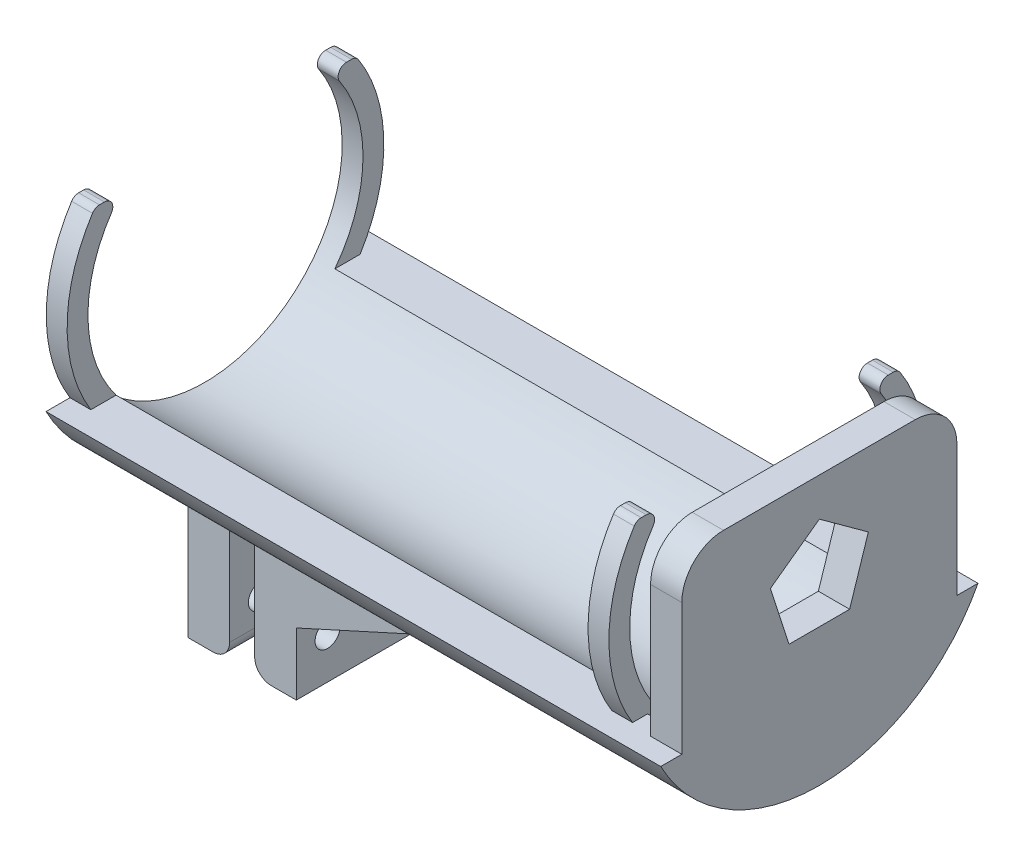
SolidWorks part; units mm, degrees
ref_plane "Front" through (0, 0, 0) normal (0, 0, 1) x (1, 0, 0)
ref_plane "Top" through (0, 0, 0) normal (0, 1, 0) x (1, 0, 0)
ref_plane "Right" through (0, 0, 0) normal (1, 0, 0) x (0, 0, -1)
sketch "Sketch1" plane through (0, 0, 0) normal (1, 0, 0) x (0, 0, -1)
  line L1 (-38.0657, -20) -> (-26.2488, -20)
  line L2 (26.2488, -20) -> (38.0657, -20)
  arc A0 (-26.2488, -20) -> (26.2488, -20) centre (0, 0) ccw
  arc A1 (-38.0657, -20) -> (38.0657, -20) centre (0, 0) ccw
  dimension "D1" = 66
  dimension "D2" = 10
  dimension "D3" = 20
extrude "Boss-Extrude1" add sketch "Sketch1" along normal mid plane 140
sketch "Sketch2" plane through (70, 0, 0) normal (1, 0, 0) x (0, 0, -1)
  line L0 (-31.305, 21.5407) -> (-25, 21.5407)
  line L1 (25, 21.5407) -> (31.305, 21.5407)
  arc A0 (-25, 21.5407) -> (25, 21.5407) centre (0, 0) ccw
  arc A1 (-31.305, 21.5407) -> (31.305, 21.5407) centre (0, 0) ccw
  dimension "D1" = 5
  dimension "D2" = 50
extrude "Boss-Extrude2" add sketch "Sketch2" against normal blind 5 from offset 5 offset against normal yes
sketch "Sketch3" plane through (70, 0, 0) normal (1, 0, 0) x (0, 0, -1)
  line L3 (-25, 21.5407) -> (-31.305, 21.5407) construction
  line L4 (38.0657, -20) -> (26.2488, -20)
  line L5 (-33, -20) -> (-33, 11.5407)
  line L6 (-23, 21.5407) -> (23, 21.5407)
  line L7 (-26.2488, -20) -> (-38.0657, -20)
  line L8 (38.0657, -20) -> (33, -20)
  line L11 (-33, -20) -> (-38.0657, -20)
  line L12 (31.305, 21.5407) -> (25, 21.5407) construction
  line L13 (33, 11.5407) -> (33, -20)
  arc A0 (-25, 21.5407) -> (-26.2488, -20) centre (0, 0) ccw construction
  arc A1 (26.2488, -20) -> (25, 21.5407) centre (0, 0) ccw construction
  arc A2 (23, 21.5407) -> (33, 11.5407) centre (23, 11.5407) cw
  arc A3 (-33, 11.5407) -> (-23, 21.5407) centre (-23, 11.5407) cw
  arc A5 (-26.2488, -20) -> (26.2488, -20) centre (0, 0) ccw
  arc A7 (-38.0657, -20) -> (38.0657, -20) centre (0, 0) ccw
  arc A11 (-38.0657, -20) -> (38.0657, -20) centre (0, 0) ccw
  point P24 (33, 21.5407)
  point P27 (-33, 21.5407)
  dimension "D2" = 10
  dimension "D1" = 0
extrude "Boss-Extrude3" add sketch "Sketch3" along normal blind 7.5
sketch "Sketch4" plane through (0, 0, 0) normal (0, 0, 1) x (1, 0, 0)
  line L0 (-49, -43) -> (-49, -69)
  line L1 (-70, -43) -> (77.5, -43) construction
  line L2 (-53, -73) -> (-59, -73)
  line L3 (-59, -73) -> (-59, -43)
  line L4 (-46, -43) -> (-46, -73) construction
  line L5 (-59, -43) -> (-49, -43)
  line L6 (-70, -20) -> (-70, -43) construction
  line L7 (-33, -43) -> (-43, -43)
  line L9 (-39, -73) -> (-33, -73)
  line L10 (-43, -43) -> (-43, -69)
  line L11 (-33, -58) -> (0, -43)
  line L12 (-70, -43) -> (77.5, -43) construction
  line L13 (-33, -43) -> (0, -43)
  line L14 (-33, -58) -> (-33, -73)
  arc A0 (-39, -73) -> (-43, -69) centre (-39, -69) cw
  arc A1 (-49, -69) -> (-53, -73) centre (-53, -69) cw
  point P16 (-43, -73)
  point P19 (-49, -73)
  dimension "D5" = 4
  dimension "D1" = 24
  dimension "D2" = 3
  dimension "D3" = 10
  dimension "D4" = 30
  dimension "D6" = 15
extrude "Boss-Extrude4" add sketch "Sketch4" along normal mid plane 30 separate body
sketch "Sketch5" plane through (0, -43, 0) normal (0, 1, 0) x (1, 0, 0)
  line L0 (0, 15) -> (-43, 15) construction
  line L1 (-43, 15) -> (-43, -15) construction
  line L2 (-43, -15) -> (0, -15) construction
  line L4 (-49, 15) -> (-59, 15) construction
  line L5 (-59, 15) -> (-59, -15) construction
  line L6 (-59, -15) -> (-49, -15) construction
  line L7 (-49, -15) -> (-49, 15) construction
  line L8 (0, 15) -> (-43, 15)
  line L9 (-43, 15) -> (-43, -15)
  line L10 (-43, -15) -> (0, -15)
  line L11 (0, -15) -> (0, 15)
  line L12 (-49, 15) -> (-59, 15)
  line L13 (-59, 15) -> (-59, -15)
  line L14 (-59, -15) -> (-49, -15)
  line L15 (-49, -15) -> (-49, 15)
extrude "Boss-Extrude6" add sketch "Sketch5" along normal up to surface up to face at (3.75, -31.5, 0)
sketch "Sketch6" plane through (-59, 0, 0) normal (-1, 0, 0) x (0, 0, 1)
  line L0 (0, -43) -> (0, -73) construction
  line L1 (15, -73) -> (-15, -73) construction
  arc A0 (-15, -40.2989) -> (15, -40.2989) centre (0, 0) ccw construction
  circle A1 centre (-7.5, -63) radius 3
  circle A2 centre (7.5, -63) radius 3
  dimension "D2" = 6
  dimension "D1" = 7.5
  dimension "D3" = 10
extrude "Cut-Extrude1" cut sketch "Sketch6" against normal up to surface (26 mm away) up to face at (-33, -65.5, 0)
sketch "Sketch7" plane through (70, 0, 0) normal (-1, 0, 0) x (0, 0, 1)
  circle A0 centre (0, 0) radius 35
  dimension "D1" = 70
extrude "Cut-Extrude2" cut sketch "Sketch7" along normal up to surface (5 mm away) up to face at (65, 0.8631, 32.1016)
pattern_linear "LPattern1" count 2 spacing 130 along (-1, 0, 0) of "Boss-Extrude2"
fillet "Fillet1" radius 2 8 edges at (62.5, 21.5407, 25) (62.5, 21.5407, -25) (-67.5, 21.5407, 25) (-67.5, 21.5407, 31.305) (-67.5, 21.5407, -31.305) (-67.5, 21.5407, -25) (62.5, 21.5407, 31.305) (62.5, 21.5407, -31.305)
sketch "Sketch8" plane through (70, 0, 0) normal (-1, 0, 0) x (0, 0, 1)
  line L0 (0, 0) -> (0, 12.3607) construction
  line L1 (0, 12.3607) -> (-11.7557, 3.8197)
  line L2 (-11.7557, 3.8197) -> (-7.2654, -10)
  line L3 (-7.2654, -10) -> (7.2654, -10)
  line L4 (7.2654, -10) -> (11.7557, 3.8197)
  line L5 (11.7557, 3.8197) -> (0, 12.3607)
  circle A0 centre (0, 0) radius 10 construction
  dimension "D1" = 20
extrude "Cut-Extrude3" cut sketch "Sketch8" against normal up to next
